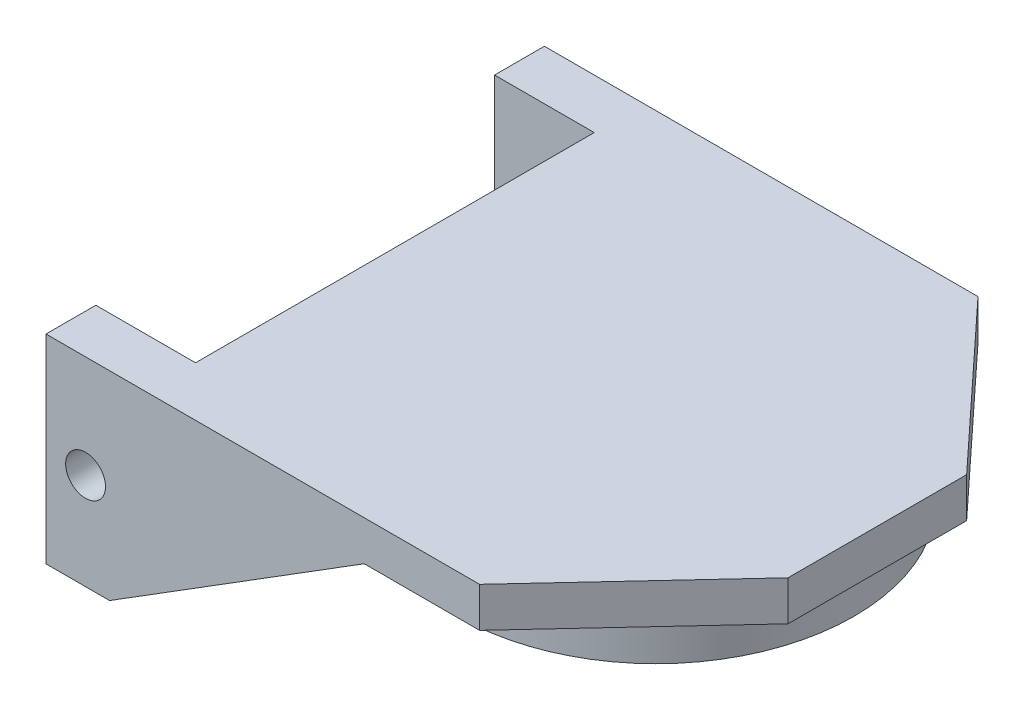
SolidWorks part; units mm, degrees
material "PBT General Purpose"
ref_plane "Front Plane" through (0, 0, 0) normal (0, 0, 1) x (1, 0, 0)
ref_plane "Top Plane" through (0, 0, 0) normal (0, 1, 0) x (1, 0, 0)
ref_plane "Right Plane" through (0, 0, 0) normal (1, 0, 0) x (0, 0, -1)
sketch "Sketch1" plane through (0, 0, 0) normal (0, 1, 0) x (1, 0, 0)
  line L1 (0, 0) -> (26, 0)
  line L2 (0, 0) -> (0, 25)
  line L3 (0, 25) -> (26, 25)
  line L4 (26, 0) -> (26, 25)
  line L5 (0, 22.5) -> (5, 22.5)
  line L6 (0, 22.5) -> (0, 2.5)
  line L7 (0, 2.5) -> (5, 2.5)
  line L8 (5, 22.5) -> (5, 2.5)
  dimension "D1" = 26
  dimension "D2" = 25
  dimension "D3" = 2.5
  dimension "D4" = 2.5
  dimension "D5" = 5
extrude "Boss-Extrude1" add sketch "Sketch1" along normal blind 2 contours L5 L8 L7 L2 L1 L4 L3
sketch "Sketch2" plane through (0, 2, 0) normal (0, 1, 0) x (1, 0, 0)
  line L0 (26, 25) -> (40.5792, 15.4966)
  line L1 (40.5792, 15.4966) -> (40.5792, 9.1986)
  line L2 (40.5792, 9.1986) -> (26, 0)
  line L3 (26, 12.5) -> (40.5792, 12.3476) construction
  line L4 (26, 0) -> (26, 25) construction
  line L5 (26, 25) -> (26, 0)
  dimension "D1" = 14.5792
extrude "Boss-Extrude2" add sketch "Sketch2" against normal blind 2
sketch "Sketch3" plane through (0, 0, 0) normal (0, 0, 1) x (1, 0, 0)
  line L0 (0, 0) -> (0, -7.9861)
  line L1 (0, -7.9861) -> (3.1878, -7.9861)
  line L2 (3.1878, -7.9861) -> (15.963, 0)
  line L3 (0, 0) -> (26, 0) construction
  circle A0 centre (1.9845, -4.6579) radius 1
  line M1 (0, 0) -> (26, 0)
  dimension "D1" = 2
extrude "Boss-Extrude3" add sketch "Sketch3" against normal blind 2.5 contours L1 L2 L0 A0 M1
sketch "Sketch4" plane through (0, 0, -25) normal (0, 0, -1) x (-1, 0, 0)
  line L0 (0, 0) -> (0, -7.9861)
  line L1 (0, -7.9861) -> (-3.1878, -7.9861)
  line L2 (-3.1878, -7.9861) -> (-15.963, 0)
  circle A1 centre (-1.9845, -4.6579) radius 1
sketch "Sketch5" plane through (0, 0, 0) normal (0, 0, 1) x (1, 0, 0)
  circle A0 centre (1.9845, -4.6579) radius 1
extrude "Boss-Extrude5" add sketch "Sketch5" against normal blind 2.5
sketch "Sketch6" plane through (0, 0, 0) normal (0, 0, 1) x (1, 0, 0)
  circle A0 centre (1.9845, -3.1467) radius 1
  dimension "D1" = 2
extrude "Cut-Extrude1" cut sketch "Sketch6" against normal blind 2.5
sketch "Sketch7" plane through (0, 0, -25) normal (0, 0, -1) x (-1, 0, 0)
  circle A0 centre (-1.9845, -3.1467) radius 1
sketch "Sketch8" plane through (0, 0, -25) normal (0, 0, -1) x (-1, 0, 0)
  line L0 (0, 0) -> (0, -7.9861)
  line L1 (0, -7.9861) -> (-3.1878, -7.9861)
  line L2 (-3.1878, -7.9861) -> (-15.963, 0)
  line L3 (-15.963, 0) -> (0, 0)
  circle A0 centre (-1.9845, -3.1467) radius 1
extrude "Boss-Extrude6" add sketch "Sketch8" against normal blind 2.5
sketch "Sketch9" plane through (0, 2, 0) normal (0, 1, 0) x (1, 0, 0)
  line L0 (21.7489, 25) -> (29.1989, 16.9803)
  line L1 (0, 25) -> (26, 25) construction
  line L2 (29.1989, 16.9803) -> (29.1989, 8.0197)
  line L3 (29.1989, 8.0197) -> (21.7489, 0)
  line L4 (0, 0) -> (26, 0) construction
  line L5 (21.7489, 25) -> (26, 25)
  line L6 (26, 25) -> (40.5792, 15.4966)
  line L7 (40.5792, 15.4966) -> (40.5792, 9.1986)
  line L8 (40.5792, 9.1986) -> (26, 0)
  line L9 (26, 0) -> (21.7489, 0)
extrude "Cut-Extrude2" cut sketch "Sketch9" against normal blind 2.5
sketch "Sketch10" plane through (0, 0, 0) normal (0, -1, 0) x (1, 0, 0)
  circle A1 centre (18.0898, -12.5) radius 9.9416
  circle A2 centre (18.0898, -12.5) radius 9.5
  dimension "D1" = 19
extrude "Boss-Extrude9" add sketch "Sketch10" along normal blind 2.5
